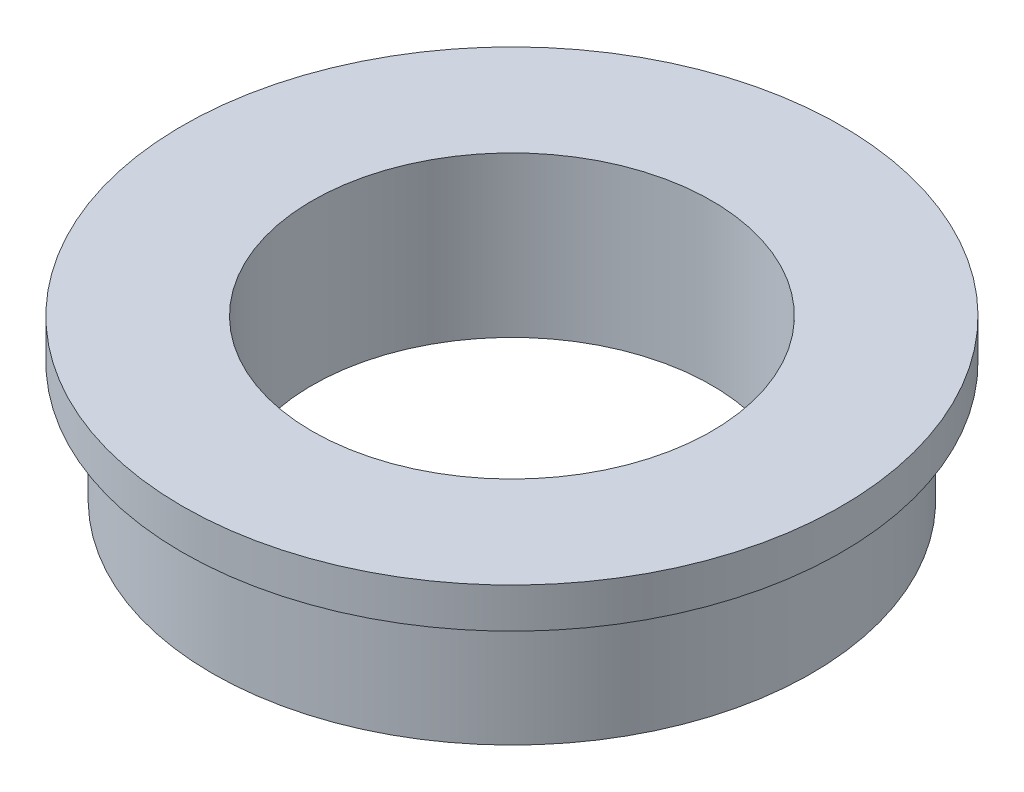
SolidWorks part; units mm, degrees
ref_plane "前视基准面" through (0, 0, 0) normal (0, 0, 1) x (1, 0, 0)
ref_plane "上视基准面" through (0, 0, 0) normal (0, 1, 0) x (1, 0, 0)
ref_plane "右视基准面" through (0, 0, 0) normal (1, 0, 0) x (0, 0, -1)
sketch "Sketch1" plane through (0, 0, 0) normal (1, 0, 0) x (0, 0, -1)
  line L1 (8.25, -2.0677) -> (8.25, -3.0677)
  line L2 (8.25, -3.0677) -> (7.5, -3.0677)
  line L3 (7.5, -3.0677) -> (7.5, -6.0677)
  line L4 (7.5, -6.0677) -> (5, -6.0677)
  line L5 (5, -6.0677) -> (5, -2.0677)
  line L7 (8.25, -2.0677) -> (5, -2.0677)
  line L8 (0, 4.0059) -> (0, -9.514) construction
  dimension "D1" = 7.5
  dimension "D2" = 5
  dimension "D3" = 8.25
  dimension "D4" = 3
  dimension "D5" = 1
revolve "Revolve1" add sketch "Sketch1" angle 360 about L8
